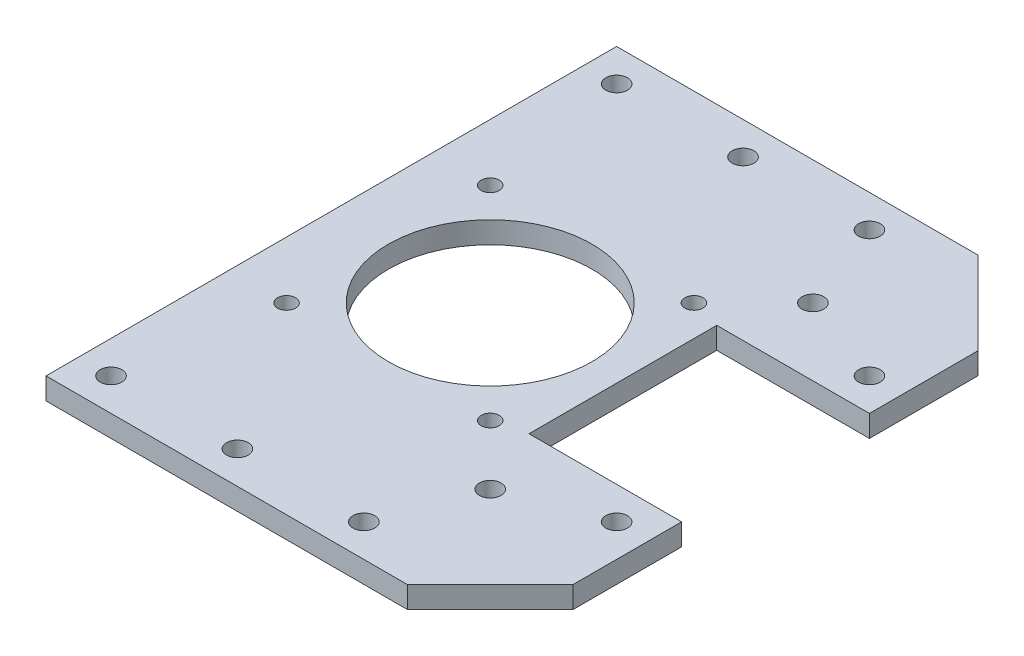
SolidWorks part; units mm, degrees
ref_plane "前视基准面" through (0, 0, 0) normal (0, 0, 1) x (1, 0, 0)
ref_plane "上视基准面" through (0, 0, 0) normal (0, 1, 0) x (1, 0, 0)
ref_plane "右视基准面" through (0, 0, 0) normal (1, 0, 0) x (0, 0, -1)
other "Configuration Table"
sketch "草图1" plane through (0, 0, 0) normal (0, 1, 0) x (1, 0, 0)
  line L5 (-37.5, 37.5) -> (37.5, -37.5) construction
  line L6 (-37.5, -37.5) -> (37.5, 37.5) construction
  line L11 (-14.1, 14.1) -> (14.1, 14.1) construction
  line L12 (-14.1, 14.1) -> (-14.1, -14.1) construction
  line L13 (-14.1, -14.1) -> (14.1, -14.1) construction
  line L14 (14.1, 14.1) -> (14.1, -14.1) construction
  line L15 (-14.1, 14.1) -> (14.1, -14.1) construction
  line L16 (-14.1, -14.1) -> (14.1, 14.1) construction
  line L18 (-37.5, 0) -> (37.5, 0) construction
  line L30 (39.5, 13) -> (18.3705, 12.9913)
  line L31 (39.5, 13) -> (39.5, 28.0315)
  line L32 (39.5, 28.0315) -> (28.0315, 39.5)
  line L33 (28.0315, 39.5) -> (-22, 39.5)
  line L34 (-22, 39.5) -> (-22, 30.5)
  line L35 (-22, 30.5) -> (-22, -39.5)
  line L36 (-22, -39.5) -> (28.0315, -39.5)
  line L37 (28.0315, -39.5) -> (39.5, -28.0315)
  line L38 (39.5, -28.0315) -> (39.5, -13)
  line L39 (18.3705, -13) -> (39.5, -13)
  line L40 (18.3705, 12.9913) -> (18.3705, -13)
  circle A3 centre (17.5, 35) radius 1.5
  circle A4 centre (22.3377, 22.3377) radius 1.5
  circle A5 centre (35, 17.5) radius 1.5
  circle A9 centre (17.5, -35) radius 1.5
  circle A10 centre (22.3377, -22.3377) radius 1.5
  circle A11 centre (35, -17.5) radius 1.5
  circle A12 centre (-14.1, 14.1) radius 1.25
  circle A13 centre (14.1, -14.1) radius 1.25
  circle A14 centre (0, 35) radius 1.5
  circle A15 centre (-17.5, 35) radius 1.5
  circle A16 centre (0, -35) radius 1.5
  circle A17 centre (-17.5, -35) radius 1.5
  circle A18 centre (14.1, 14.1) radius 1.25
  circle A19 centre (-14.1, -14.1) radius 1.25
  circle A20 centre (0, 0) radius 14.1
  circle A22 centre (0, 0) radius 22.5 construction
  point P0 (0, 0)
  point P58 (0, 0)
  dimension "D5" = 2.5
  dimension "D6" = 2.5
  dimension "D9" = 2.5
  dimension "D10" = 2.5
  dimension "D1" = 75
  dimension "D2" = 75
  dimension "D3" = 28.2
  dimension "D4" = 28.2
  dimension "D7" = 3
extrude "凸台-拉伸1" add sketch "草图1" along normal blind 3
